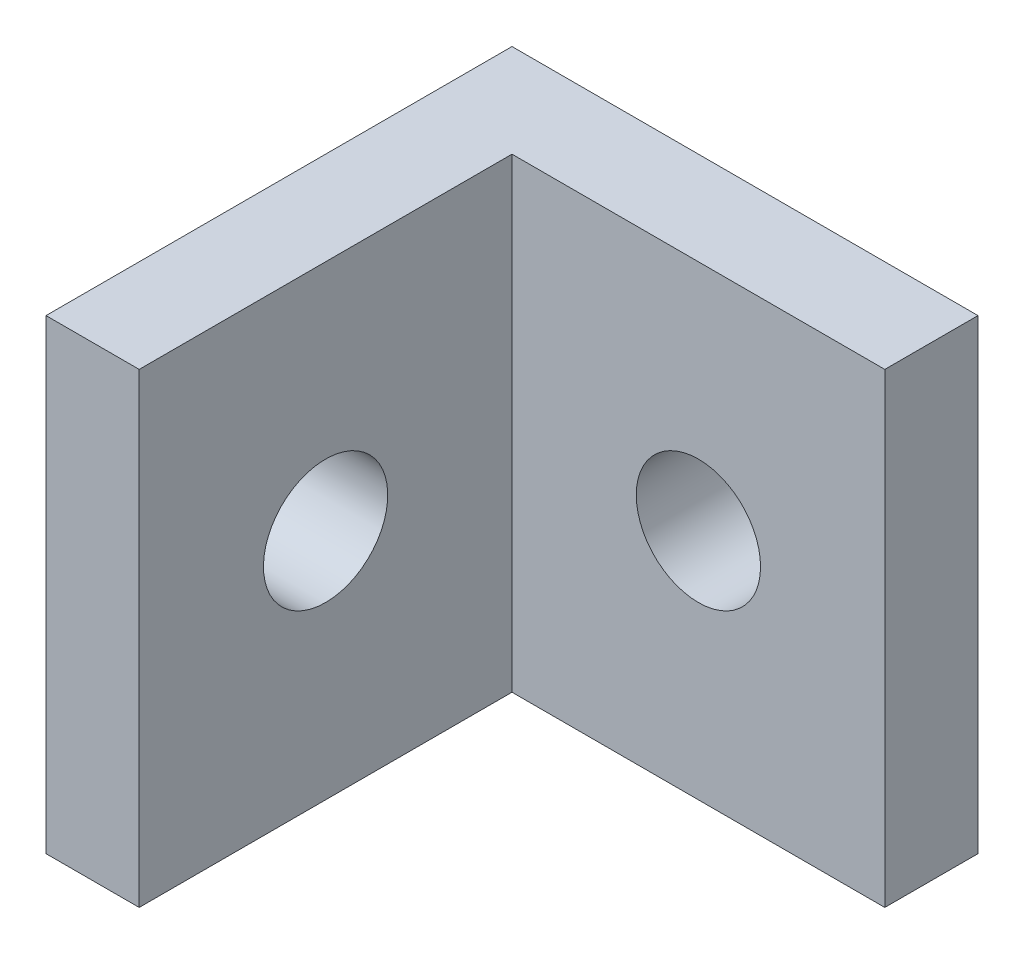
SolidWorks part; units mm, degrees
ref_plane "Front Plane" through (0, 0, 0) normal (0, 0, 1) x (1, 0, 0)
ref_plane "Top Plane" through (0, 0, 0) normal (0, 1, 0) x (1, 0, 0)
ref_plane "Right Plane" through (0, 0, 0) normal (1, 0, 0) x (0, 0, -1)
sketch "Sketch1" plane through (0, 0, 0) normal (0, 0, 1) x (1, 0, 0)
  line L1 (-7.5, 7.5) -> (7.5, 7.5)
  line L2 (-7.5, 7.5) -> (-7.5, -7.5)
  line L3 (-7.5, -7.5) -> (7.5, -7.5)
  line L4 (7.5, 7.5) -> (7.5, -7.5)
  line L5 (-7.5, 7.5) -> (7.5, -7.5) construction
  line L6 (-7.5, -7.5) -> (7.5, 7.5) construction
  point P0 (0, 0)
  dimension "D1" = 15
  dimension "D2" = 15
extrude "Boss-Extrude1" add sketch "Sketch1" along normal blind 3
sketch "Sketch2" plane through (0, 0, 3) normal (0, 0, 1) x (1, 0, 0)
  line L0 (-7.5, -7.5) -> (7.5, -7.5) construction
  line L1 (-7.5, 7.5) -> (-4.5, 7.5)
  line L2 (-7.5, 7.5) -> (-7.5, -7.5)
  line L3 (-7.5, -7.5) -> (-4.5, -7.5)
  line L4 (-4.5, 7.5) -> (-4.5, -7.5)
  dimension "D1" = 3
extrude "Boss-Extrude2" add sketch "Sketch2" along normal blind 12
sketch "Sketch3" plane through (0, 0, 0) normal (0, 0, -1) x (-1, 0, 0)
  line L0 (-7.5, -7.5) -> (-7.5, 7.5) construction
  circle A0 centre (-1.5, 0) radius 2
  dimension "D1" = 4
  dimension "D2" = 6
extrude "Cut-Extrude1" cut sketch "Sketch3" against normal blind 12
sketch "Sketch4" plane through (-7.5, 0, 0) normal (-1, 0, 0) x (0, 0, 1)
  line L0 (15, 7.5) -> (0, 7.5) construction
  line L1 (15, 7.5) -> (15, -7.5) construction
  circle A0 centre (9, 0) radius 2
  dimension "D1" = 4
  dimension "D2" = 7.5
  dimension "D3" = 6
extrude "Cut-Extrude2" cut sketch "Sketch4" against normal blind 12
